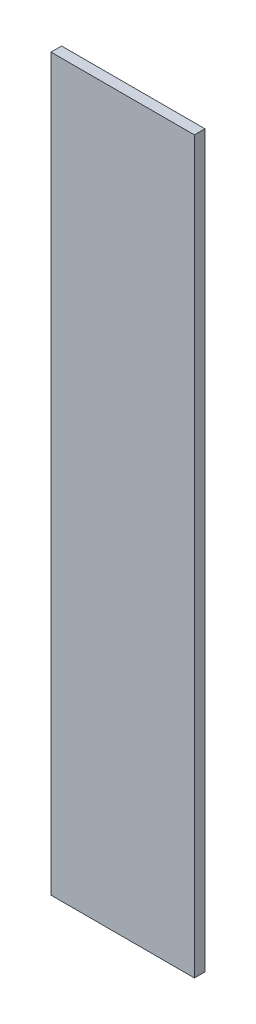
SolidWorks part; units mm, degrees
material "BUTYL"
ref_plane "Front Plane" through (0, 0, 0) normal (0, 0, 1) x (1, 0, 0)
ref_plane "Top Plane" through (0, 0, 0) normal (0, 1, 0) x (1, 0, 0)
ref_plane "Right Plane" through (0, 0, 0) normal (1, 0, 0) x (0, 0, -1)
sketch "Sketch1" plane through (0, 0, 0) normal (0, 0, 1) x (1, 0, 0)
  line L1 (0, 0) -> (13.7914, 0)
  line L2 (0, 0) -> (0, 70.2418)
  line L3 (0, 70.2418) -> (13.7914, 70.2418)
  line L4 (13.7914, 0) -> (13.7914, 70.2418)
  dimension "D1" = 13.7914
  dimension "D2" = 70.2418
extrude "Boss-Extrude1" add sketch "Sketch1" along normal blind 1.016 contours L2 L3 L4 L1
equation "\"compstripwidth\" = 0.5 + 0.04296875in"
equation "\"compstriplength\" = 2.546580364 + 0.21884675in"
equation "\"compdepth\"= 0.04in"
equation "\"D1@Sketch1\"=\"compstripwidth\""
equation "\"D2@Sketch1\"=\"compstriplength\""
equation "\"D1@Boss-Extrude1\"=\"compdepth\""
